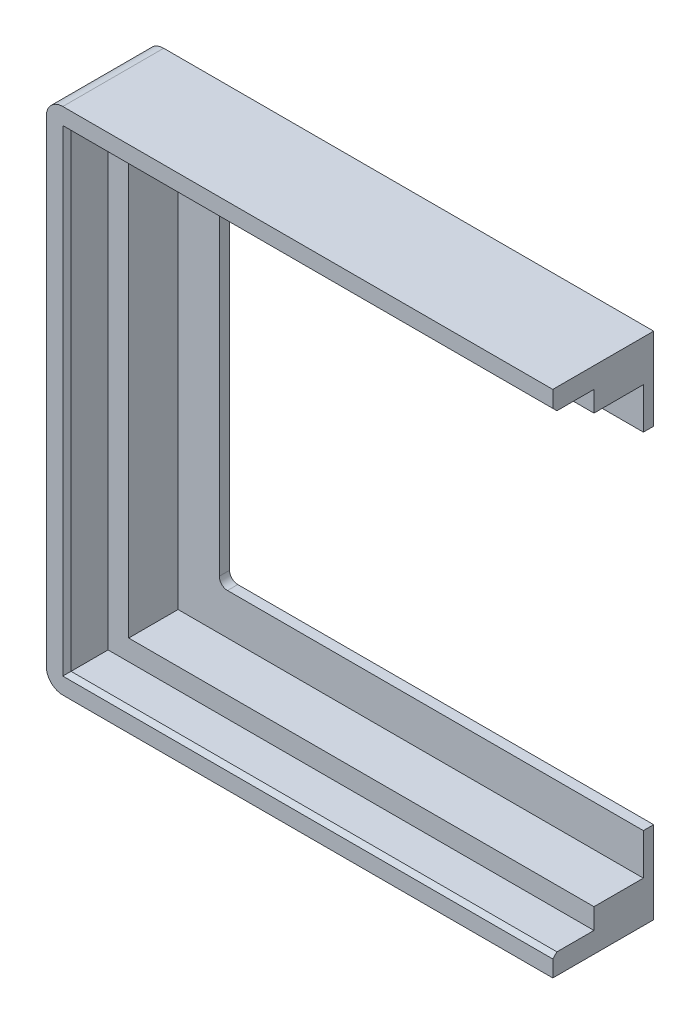
SolidWorks part; units mm, degrees
ref_plane "Front Plane" through (0, 0, 0) normal (0, 0, 1) x (1, 0, 0)
ref_plane "Top Plane" through (0, 0, 0) normal (0, 1, 0) x (1, 0, 0)
ref_plane "Right Plane" through (0, 0, 0) normal (1, 0, 0) x (0, 0, -1)
sketch "Sketch1" plane through (0, 0, 0) normal (0, 0, 1) x (1, 0, 0)
  line L0 (74.93, 72.263) -> (74.93, 78.613)
  line L1 (74.93, -72.263) -> (-74.93, -72.263)
  line L2 (74.93, -72.263) -> (74.93, 72.263)
  line L3 (74.93, 72.263) -> (-74.93, 72.263)
  line L4 (-74.93, -72.263) -> (-74.93, 72.263)
  line L5 (74.93, -72.263) -> (-74.93, 72.263) construction
  line L6 (74.93, 72.263) -> (-74.93, -72.263) construction
  line L7 (74.93, -78.613) -> (-81.28, -78.613)
  line L9 (74.93, 78.613) -> (-81.28, 78.613)
  line L10 (-81.28, -78.613) -> (-81.28, 78.613)
  line L11 (74.93, -72.4714) -> (-81.28, 78.613) construction
  line L12 (74.93, 72.4714) -> (-81.28, -78.613) construction
  line L13 (74.93, -72.263) -> (74.93, -78.613)
  point P0 (0, 0)
  point P6 (0, 0)
  dimension "D1" = 144.526
  dimension "D2" = 149.86
  dimension "D3" = 6.35
  dimension "D4" = 6.35
  dimension "D5" = 6.35
extrude "Boss-Extrude1" add sketch "Sketch1" along normal blind 12.7 contours L13 L1 L4 L3 L0 L9 L10 L7
sketch "Sketch2" plane through (0, 0, 0) normal (0, 0, -1) x (-1, 0, 0)
  line L0 (-74.93, -65.913) -> (-74.93, -78.613)
  line L1 (81.28, 78.613) -> (-74.93, 78.613)
  line L2 (81.28, 78.613) -> (81.28, -78.613)
  line L3 (81.28, -78.613) -> (-74.93, -78.613)
  line L4 (-74.93, 78.613) -> (-74.93, 65.913)
  line L5 (-74.93, 65.913) -> (68.58, 65.913)
  line L7 (-74.93, -65.913) -> (68.58, -65.913)
  line L8 (68.58, 65.913) -> (68.58, -65.913)
  dimension "D1" = 12.7
  dimension "D2" = 12.7
  dimension "D3" = 12.7
extrude "Boss-Extrude2" add sketch "Sketch2" along normal blind 15.24
sketch "Sketch3" plane through (0, 0, -15.24) normal (0, 0, -1) x (-1, 0, 0)
  line L0 (-74.93, -53.213) -> (-74.93, -78.613)
  line L1 (81.28, 78.613) -> (-74.93, 78.613)
  line L2 (81.28, 78.613) -> (81.28, -78.613)
  line L3 (81.28, -78.613) -> (-74.93, -78.613)
  line L4 (-74.93, 78.613) -> (-74.93, 53.213)
  line L5 (-74.93, 53.213) -> (55.88, 53.213)
  line L7 (-74.93, -53.213) -> (55.88, -53.213)
  line L8 (55.88, 53.213) -> (55.88, -53.213)
  dimension "D1" = 25.4
  dimension "D2" = 25.4
  dimension "D3" = 25.4
extrude "Boss-Extrude3" add sketch "Sketch3" along normal blind 3.175
fillet "Fillet1" radius 5.08 2 edges at (-81.28, -78.613, -2.8575) (-81.28, 78.613, -2.8575)
fillet "Fillet3" radius 2.54 2 edges at (-55.88, -53.213, -16.8275) (-55.88, 53.213, -16.8275)
chamfer "Chamfer2" distance 1.27 angle 45 3 edges at (0, -72.263, 12.7) (-74.93, 0, 12.7) (0, 72.263, 12.7)
